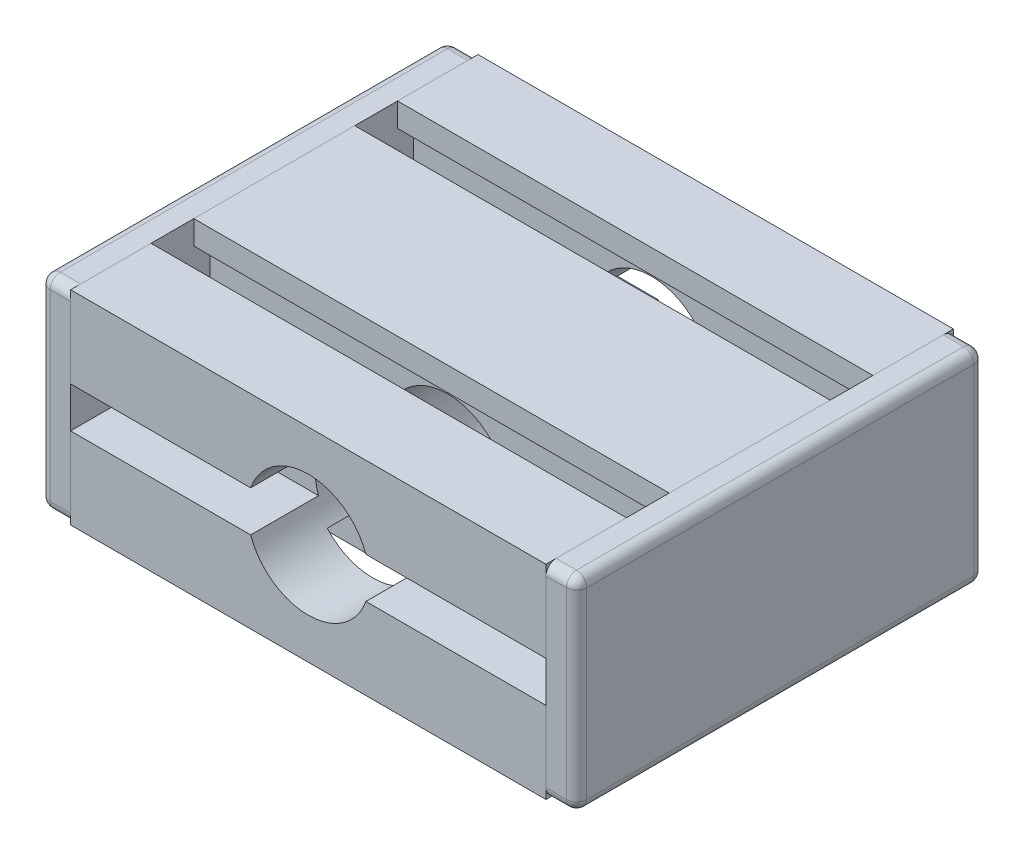
SolidWorks part; units mm, degrees
ref_plane "Front Plane" through (0, 0, 0) normal (0, 0, 1) x (1, 0, 0)
ref_plane "Top Plane" through (0, 0, 0) normal (0, 1, 0) x (1, 0, 0)
ref_plane "Right Plane" through (0, 0, 0) normal (1, 0, 0) x (0, 0, -1)
sketch "Sketch1" plane through (0, 0, 0) normal (1, 0, 0) x (0, 0, -1)
  line L0 (11.85, 0) -> (-11.85, 0)
  line L1 (-11.85, 0) -> (-11.85, 3.5)
  line L2 (-11.85, 3.5) -> (-9.5, 3.5)
  line L3 (-9.5, 3.5) -> (-9.5, 9)
  line L4 (-9.5, 9) -> (-20.5, 9)
  line L5 (-20.5, 9) -> (-20.5, 3.5)
  line L6 (-20.5, 3.5) -> (-18.15, 3.5)
  line L7 (-18.15, 3.5) -> (-18.15, 0)
  line L8 (-18.15, 0) -> (-30, 0)
  line L9 (-30, 0) -> (-30, 12)
  line L10 (-30, 12) -> (-20, 12)
  line L11 (-20, 12) -> (-20, 18)
  line L12 (-20, 15) -> (0, 15) construction
  line L13 (0, 15) -> (0, 0) construction
  line L14 (-18.15, 0) -> (-11.85, 0) construction
  line L15 (-15, 0) -> (-15, 9) construction
  line L16 (-15, 30) -> (-15, 21) construction
  line L17 (-18.15, 30) -> (-11.85, 30) construction
  line L18 (-20.5, 26.5) -> (-18.15, 26.5)
  line L19 (-11.85, 26.5) -> (-9.5, 26.5)
  line L20 (-30, 18) -> (-20, 18)
  line L21 (-30, 30) -> (-30, 18)
  line L22 (-18.15, 30) -> (-30, 30)
  line L23 (-18.15, 26.5) -> (-18.15, 30)
  line L24 (-20.5, 21) -> (-20.5, 26.5)
  line L25 (-9.5, 21) -> (-20.5, 21)
  line L26 (-9.5, 26.5) -> (-9.5, 21)
  line L27 (-11.85, 30) -> (-11.85, 26.5)
  line L28 (11.85, 30) -> (-11.85, 30)
  line L29 (11.85, 26.5) -> (9.5, 26.5)
  line L30 (20.5, 26.5) -> (18.15, 26.5)
  line L31 (18.15, 30) -> (11.85, 30) construction
  line L32 (15, 30) -> (15, 21) construction
  line L33 (15, 0) -> (15, 9) construction
  line L34 (18.15, 0) -> (11.85, 0) construction
  line L35 (20.5, 3.5) -> (18.15, 3.5)
  line L36 (11.85, 3.5) -> (9.5, 3.5)
  line L37 (11.85, 30) -> (11.85, 26.5)
  line L38 (9.5, 26.5) -> (9.5, 21)
  line L39 (9.5, 21) -> (20.5, 21)
  line L40 (20.5, 21) -> (20.5, 26.5)
  line L41 (18.15, 26.5) -> (18.15, 30)
  line L42 (18.15, 30) -> (30, 30)
  line L43 (30, 30) -> (30, 18)
  line L44 (30, 18) -> (20, 18)
  line L45 (20, 12) -> (20, 18)
  line L46 (30, 12) -> (20, 12)
  line L47 (30, 0) -> (30, 12)
  line L48 (18.15, 0) -> (30, 0)
  line L49 (18.15, 3.5) -> (18.15, 0)
  line L50 (20.5, 9) -> (20.5, 3.5)
  line L51 (9.5, 9) -> (20.5, 9)
  line L52 (9.5, 3.5) -> (9.5, 9)
  line L53 (11.85, 0) -> (11.85, 3.5)
  point P47 (0, 30)
  point P57 (0, 30)
  point P58 (0, 0)
  dimension "D1" = 9
  dimension "D2" = 6.3
  dimension "D3" = 15
  dimension "D4" = 30
  dimension "D5" = 11
  dimension "D6" = 5.5
  dimension "D7" = 3
  dimension "D8" = 10
  dimension "D9" = 15
extrude "Boss-Extrude1" add sketch "Sketch1" along normal mid plane 70
sketch "Sketch2" plane through (35, 0, 0) normal (1, 0, 0) x (0, 0, -1)
  line L1 (-30, 0) -> (30, 0)
  line L2 (-30, 0) -> (-30, 30)
  line L3 (-30, 30) -> (30, 30)
  line L4 (30, 0) -> (30, 30)
  point P4 (0, 0)
  point P6 (0, 0)
extrude "Boss-Extrude2" add sketch "Sketch2" along normal blind 4.5 separate body
sketch "Sketch3" plane through (-35, 0, 0) normal (-1, 0, 0) x (0, 0, 1)
  line L1 (-30, 0) -> (30, 0)
  line L2 (-30, 0) -> (-30, 30)
  line L3 (-30, 30) -> (30, 30)
  line L4 (30, 0) -> (30, 30)
  point P4 (30, 30)
  point P6 (-30, 0)
extrude "Boss-Extrude3" add sketch "Sketch3" along normal blind 4.5 separate body
fillet "Fillet1" radius 1.5 8 edges at (-39.5, 30, 0) (-39.5, 15, 30) (-39.5, 0, 0) (-39.5, 15, -30) (-37.25, 0, 30) (-37.25, 0, -30) (-37.25, 30, 30) (-37.25, 30, -30)
fillet "Fillet2" radius 1.5 8 edges at (39.5, 30, 0) (39.5, 15, -30) (39.5, 0, 0) (39.5, 15, 30) (37.25, 0, 30) (37.25, 0, -30) (37.25, 30, 30) (37.25, 30, -30)
sketch "Sketch4" plane through (0, 0, 0) normal (0, 0, 1) x (1, 0, 0)
  line L0 (0, 30) -> (0, 0) construction
  line L1 (35, 30) -> (-35, 30) construction
  circle A0 centre (0, 15) radius 9
  dimension "D1" = 18
extrude "Cut-Extrude1" cut sketch "Sketch4" against normal through all both and the other way through all
